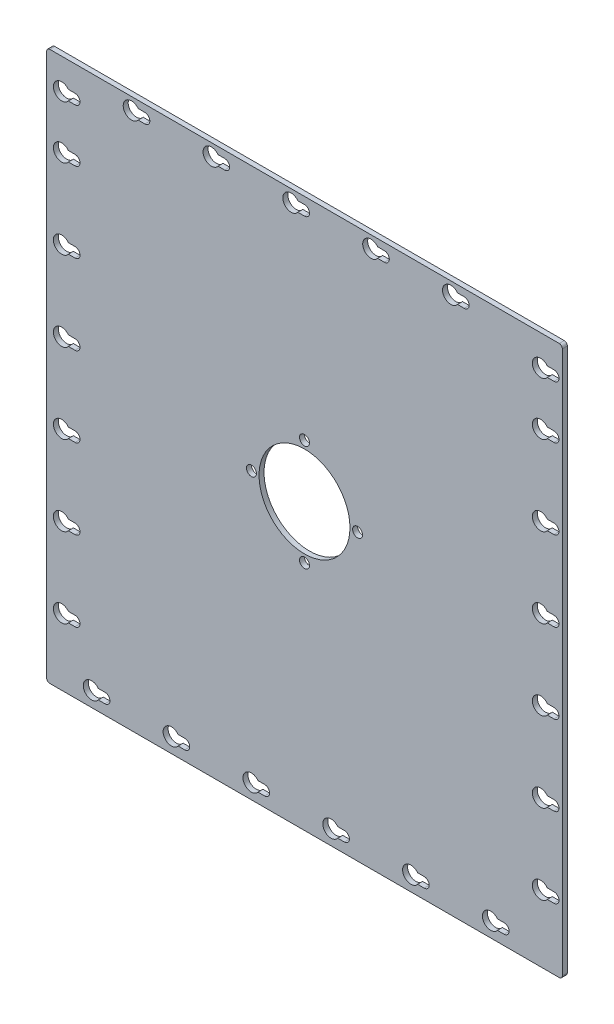
SolidWorks part; units mm, degrees
material "6061 Alloy"
ref_plane "Front Plane" through (0, 0, 0) normal (0, 0, 1) x (1, 0, 0)
ref_plane "Top Plane" through (0, 0, 0) normal (0, 1, 0) x (1, 0, 0)
ref_plane "Right Plane" through (0, 0, 0) normal (1, 0, 0) x (0, 0, -1)
sketch "Sketch1" plane through (0, 0, 0) normal (0, 0, 1) x (1, 0, 0)
  line L0 (0, 0) -> (0, -174.745)
  line L3 (0, -174.745) -> (165.1, -174.745)
  line L5 (0, 0) -> (165.1, 0)
  line L6 (165.1, -174.745) -> (165.1, 0)
  line L7 (82.55, 0) -> (82.55, -174.745) construction
  line L8 (31.75, -2.2625) -> (29.6344, -2.2625)
  line L9 (31.75, -5.4375) -> (29.6344, -5.4375)
  line L10 (9.525, -24.9325) -> (7.4094, -24.9325)
  line L11 (9.525, -28.1075) -> (7.4094, -28.1075)
  line L12 (161.925, -24.9325) -> (159.8094, -24.9325)
  line L13 (161.925, -28.1075) -> (159.8094, -28.1075)
  line L14 (57.15, -2.2625) -> (55.0344, -2.2625)
  line L15 (57.15, -5.4375) -> (55.0344, -5.4375)
  line L16 (82.55, -2.2625) -> (80.4344, -2.2625)
  line L17 (82.55, -5.4375) -> (80.4344, -5.4375)
  line L18 (107.95, -2.2625) -> (105.8344, -2.2625)
  line L19 (107.95, -5.4375) -> (105.8344, -5.4375)
  line L20 (133.35, -2.2625) -> (131.2344, -2.2625)
  line L21 (133.35, -5.4375) -> (131.2344, -5.4375)
  line L22 (9.525, -50.3325) -> (7.4094, -50.3325)
  line L23 (9.525, -53.5075) -> (7.4094, -53.5075)
  line L24 (161.925, -50.3325) -> (159.8094, -50.3325)
  line L25 (161.925, -53.5075) -> (159.8094, -53.5075)
  line L26 (9.525, -75.7325) -> (7.4094, -75.7325)
  line L27 (9.525, -78.9075) -> (7.4094, -78.9075)
  line L28 (161.925, -75.7325) -> (159.8094, -75.7325)
  line L29 (161.925, -78.9075) -> (159.8094, -78.9075)
  line L30 (9.525, -101.1325) -> (7.4094, -101.1325)
  line L31 (9.525, -104.3075) -> (7.4094, -104.3075)
  line L32 (161.925, -101.1325) -> (159.8094, -101.1325)
  line L33 (161.925, -104.3075) -> (159.8094, -104.3075)
  line L34 (9.525, -126.5325) -> (7.4094, -126.5325)
  line L35 (9.525, -129.7075) -> (7.4094, -129.7075)
  line L36 (161.925, -126.5325) -> (159.8094, -126.5325)
  line L37 (161.925, -129.7075) -> (159.8094, -129.7075)
  line L38 (9.525, -151.9325) -> (7.4094, -151.9325)
  line L39 (9.525, -155.1075) -> (7.4094, -155.1075)
  line L40 (161.925, -151.9325) -> (159.8094, -151.9325)
  line L41 (161.925, -155.1075) -> (159.8094, -155.1075)
  line L42 (19.05, -168.395) -> (16.9344, -168.395)
  line L43 (19.05, -171.57) -> (16.9344, -171.57)
  line L44 (44.45, -168.395) -> (42.3344, -168.395)
  line L45 (44.45, -171.57) -> (42.3344, -171.57)
  line L46 (69.85, -168.395) -> (67.7344, -168.395)
  line L47 (69.85, -171.57) -> (67.7344, -171.57)
  line L48 (95.25, -168.395) -> (93.1344, -168.395)
  line L49 (95.25, -171.57) -> (93.1344, -171.57)
  line L50 (120.65, -168.395) -> (118.5344, -168.395)
  line L51 (120.65, -171.57) -> (118.5344, -171.57)
  line L52 (146.05, -168.395) -> (143.9344, -168.395)
  line L53 (146.05, -171.57) -> (143.9344, -171.57)
  line L54 (0.5, 0) -> (0.5, -174.745)
  line L55 (164.6, -174.745) -> (164.6, 0)
  line L56 (161.925, -8.1) -> (159.8094, -8.1)
  line L57 (161.925, -11.275) -> (159.8094, -11.275)
  line L58 (9.525, -8.1) -> (7.4094, -8.1)
  line L59 (9.525, -11.275) -> (7.4094, -11.275)
  circle A41 centre (9.525, -153.52) radius 1.5875
  circle A42 centre (19.05, -169.9825) radius 1.5875
  circle A43 centre (9.525, -128.12) radius 1.5875
  circle A44 centre (9.525, -102.72) radius 1.5875
  circle A45 centre (9.525, -77.32) radius 1.5875
  circle A46 centre (9.525, -51.92) radius 1.5875
  circle A47 centre (9.525, -26.52) radius 1.5875
  circle A49 centre (44.45, -169.9825) radius 1.5875
  circle A50 centre (69.85, -169.9825) radius 1.5875
  circle A51 centre (95.25, -169.9825) radius 1.5875
  circle A52 centre (120.65, -169.9825) radius 1.5875
  circle A68 centre (146.05, -169.9825) radius 1.5875
  circle A69 centre (107.95, -3.85) radius 1.5875
  circle A70 centre (82.55, -3.85) radius 1.5875
  circle A71 centre (57.15, -3.85) radius 1.5875
  circle A72 centre (9.525, -1.12) radius 1.5875 [skipped]
  circle A73 centre (133.35, -3.85) radius 1.5875
  circle A74 centre (31.75, -3.85) radius 1.5875
  circle A75 centre (161.925, -26.52) radius 1.5875
  circle A76 centre (161.925, -51.92) radius 1.5875
  circle A77 centre (161.925, -77.32) radius 1.5875
  circle A78 centre (161.925, -102.72) radius 1.5875
  circle A79 centre (161.925, -128.12) radius 1.5875
  circle A80 centre (161.925, -153.52) radius 1.5875
  circle A81 centre (27.5125, -3.85) radius 2.65
  circle A83 centre (5.2875, -26.52) radius 2.65
  circle A84 centre (157.6875, -26.52) radius 2.65
  circle A85 centre (52.9125, -3.85) radius 2.65
  circle A86 centre (78.3125, -3.85) radius 2.65
  circle A87 centre (103.7125, -3.85) radius 2.65
  circle A88 centre (129.1125, -3.85) radius 2.65
  circle A89 centre (5.2875, -51.92) radius 2.65
  circle A90 centre (157.6875, -51.92) radius 2.65
  circle A91 centre (5.2875, -77.32) radius 2.65
  circle A92 centre (157.6875, -77.32) radius 2.65
  circle A93 centre (5.2875, -102.72) radius 2.65
  circle A94 centre (157.6875, -102.72) radius 2.65
  circle A95 centre (5.2875, -128.12) radius 2.65
  circle A96 centre (157.6875, -128.12) radius 2.65
  circle A97 centre (5.2875, -153.52) radius 2.65
  circle A98 centre (157.6875, -153.52) radius 2.65
  circle A99 centre (14.8125, -169.9825) radius 2.65
  circle A100 centre (40.2125, -169.9825) radius 2.65
  circle A101 centre (65.6125, -169.9825) radius 2.65
  circle A102 centre (91.0125, -169.9825) radius 2.65
  circle A103 centre (116.4125, -169.9825) radius 2.65
  circle A104 centre (141.8125, -169.9825) radius 2.65
  circle A105 centre (82.55, -84.075) radius 14.462
  circle A106 centre (82.55, -67.184) radius 1.5875
  circle A107 centre (99.441, -84.075) radius 1.5875
  circle A108 centre (65.659, -84.075) radius 1.5875
  circle A109 centre (82.55, -100.966) radius 1.5875
  circle A110 centre (67.55, -69.075) radius 3 construction
  circle A111 centre (97.55, -69.075) radius 3 construction
  circle A112 centre (97.55, -99.075) radius 3 construction
  circle A113 centre (67.55, -99.075) radius 3 construction
  circle A114 centre (9.525, -9.6875) radius 1.5875
  circle A115 centre (5.2875, -9.6875) radius 2.65
  circle A116 centre (161.925, -9.6875) radius 1.5875
  circle A117 centre (157.6875, -9.6875) radius 2.65
  dimension "D3" = 3.175
  dimension "D8" = 3.175
  dimension "D21" = 5.3
  dimension "D28" = 28.924
  dimension "D29" = 3.175
  dimension "D38" = 6
  dimension "D1" = 165.1
  dimension "D2" = 174.745
  dimension "D5" = 9.525
  dimension "D4" = 21.225
  dimension "D6" = 19.05
  dimension "D7" = 4.7625
  dimension "D9" = 25.4
  dimension "D10" = 25.4
  dimension "D15" = 25.4
  dimension "D12" = 3.85
  dimension "D13" = 31.75
  dimension "D17" = 31.75
  dimension "D18" = 3.175
  dimension "D20" = 25.4
  dimension "D23" = 25.4
  dimension "D25" = 25.4
  dimension "D27" = 25.4
  dimension "D30" = 16.891
  dimension "D31" = 16.891
  dimension "D32" = 16.891
  dimension "D33" = 16.891
  dimension "D34" = 90.67
  dimension "D35" = 0.5
  dimension "D36" = 0.5
  dimension "D37" = 30
  dimension "D39" = 30
  dimension "D40" = 15
  dimension "D41" = 15
  dimension "D42" = 9.6875
  dimension "D43" = 9.6875
  dimension "D11" = 7
  dimension "D14" = 5
  dimension "D16" = 5
  dimension "D19" = 6
  dimension "D22" = 5
  dimension "D24" = 6
  dimension "D26" = 6
extrude "Boss-Extrude1" add sketch "Sketch1" along normal blind 1.5875 contours L3 L55 L5 L54 A117 L56 A116 L57 A115 L58 A114 L59 A109 A108 A107 A106 A105 A104 L52 A68 L53 A103 L50 A52 L51 A102 L48 A51 L49 A101 L46 A50 L47 A100 L44 A49 L45 A99
fillet "Fillet1" radius 1 4 edges at (0.5, -174.745, 0.7937) (0.5, 0, 0.7937) (164.6, -174.745, 0.7937) (164.6, 0, 0.7937)
equation "\"D8@Sketch1\"=\"D3@Sketch1\""
equation "\"D43@Sketch1\"=\"D42@Sketch1\""
